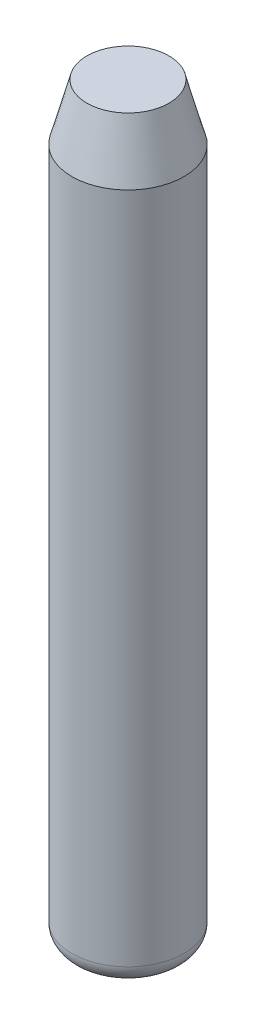
SolidWorks part; units mm, degrees
ref_plane "Front Plane" through (0, 0, 0) normal (0, 0, 1) x (1, 0, 0)
ref_plane "Top Plane" through (0, 0, 0) normal (0, 1, 0) x (1, 0, 0)
ref_plane "Right Plane" through (0, 0, 0) normal (1, 0, 0) x (0, 0, -1)
sketch "Sketch1" plane through (0, 0, 0) normal (0, 1, 0) x (1, 0, 0)
  circle A0 centre (0, 0) radius 1.5
  dimension "D1" = 3
extrude "Boss-Extrude1" add sketch "Sketch1" along normal blind 20
chamfer "Chamfer1" distance 1.5 angle 15 1 edges at (0, 20, 1.5)
fillet "Fillet1" radius 0.5 1 edges at (0, 0, 1.5)
